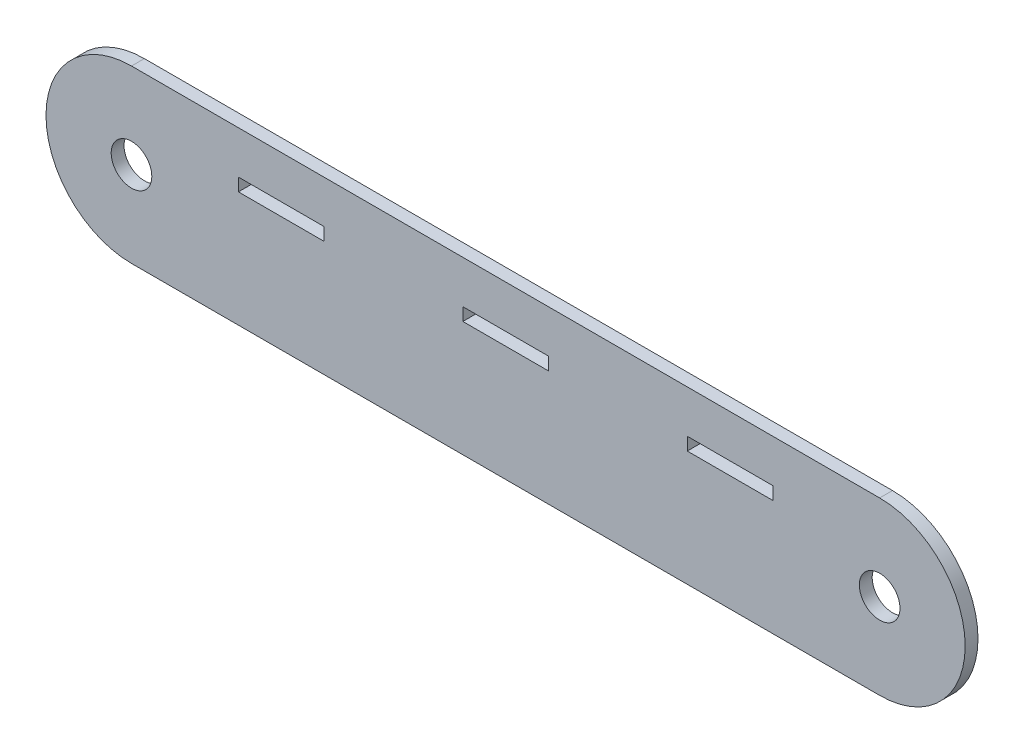
SolidWorks part; units mm, degrees
material "Mahogany"
ref_plane "Front Plane" through (0, 0, 0) normal (0, 0, 1) x (1, 0, 0)
ref_plane "Top Plane" through (0, 0, 0) normal (0, 1, 0) x (1, 0, 0)
ref_plane "Right Plane" through (0, 0, 0) normal (1, 0, 0) x (0, 0, -1)
sketch "Sketch1" plane through (0, 0, 0) normal (0, 0, 1) x (1, 0, 0)
  line L0 (-35.5297, 2.1311) -> (314.4703, 2.1311) construction
  line L1 (-35.5297, 42.1311) -> (314.4703, 42.1311)
  line L2 (-35.5297, -37.8689) -> (314.4703, -37.8689)
  line L3 (139.4703, -70.1329) -> (139.4703, 64.3952) construction
  line L4 (159.4703, 16.1311) -> (119.4703, 16.1311)
  line L5 (159.4703, 16.1311) -> (159.4703, 22.1311)
  line L6 (159.4703, 22.1311) -> (119.4703, 22.1311)
  line L7 (119.4703, 16.1311) -> (119.4703, 22.1311)
  line L8 (159.4703, 16.1311) -> (119.4703, 22.1311) construction
  line L9 (159.4703, 22.1311) -> (119.4703, 16.1311) construction
  line L14 (224.4703, 16.1311) -> (264.4703, 16.1311)
  line L15 (224.4703, 16.1311) -> (224.4703, 22.1311)
  line L16 (224.4703, 22.1311) -> (264.4703, 22.1311)
  line L17 (264.4703, 16.1311) -> (264.4703, 22.1311)
  line L18 (224.4703, 16.1311) -> (264.4703, 22.1311) construction
  line L19 (224.4703, 22.1311) -> (264.4703, 16.1311) construction
  line L20 (54.4703, 16.1311) -> (14.4703, 16.1311)
  line L21 (54.4703, 16.1311) -> (54.4703, 22.1311)
  line L22 (54.4703, 22.1311) -> (14.4703, 22.1311)
  line L23 (14.4703, 16.1311) -> (14.4703, 22.1311)
  line L24 (54.4703, 16.1311) -> (14.4703, 22.1311) construction
  line L25 (54.4703, 22.1311) -> (14.4703, 16.1311) construction
  line L26 (-35.5297, 2.1311) -> (-35.5297, 22.1311) construction
  line L27 (-35.5297, 22.1311) -> (314.4703, 22.1311) construction
  line L28 (314.4703, 22.1311) -> (314.4703, 2.1311) construction
  arc A0 (-35.5297, 42.1311) -> (-35.5297, -37.8689) centre (-35.5297, 2.1311) ccw
  arc A1 (314.4703, -37.8689) -> (314.4703, 42.1311) centre (314.4703, 2.1311) ccw
  circle A2 centre (-35.5297, 2.1311) radius 9.5
  circle A3 centre (314.4703, 2.1311) radius 9.5
  point P3 (139.4703, 2.1311)
  point P22 (34.4703, 19.1311)
  dimension "D9" = 19
  dimension "D10" = 19
  dimension "D2" = 6
  dimension "D3" = 175
  dimension "D4" = 40
  dimension "D5" = 6
  dimension "D6" = 6
  dimension "D7" = 40
  dimension "D8" = 80
  dimension "D11" = 40
  dimension "D12" = 175
  dimension "D13" = 20
  dimension "D14" = 65
  dimension "D15" = 65
  dimension "D16" = 50
  dimension "D17" = 50
extrude "Boss-Extrude1" add sketch "Sketch1" along normal blind 6
